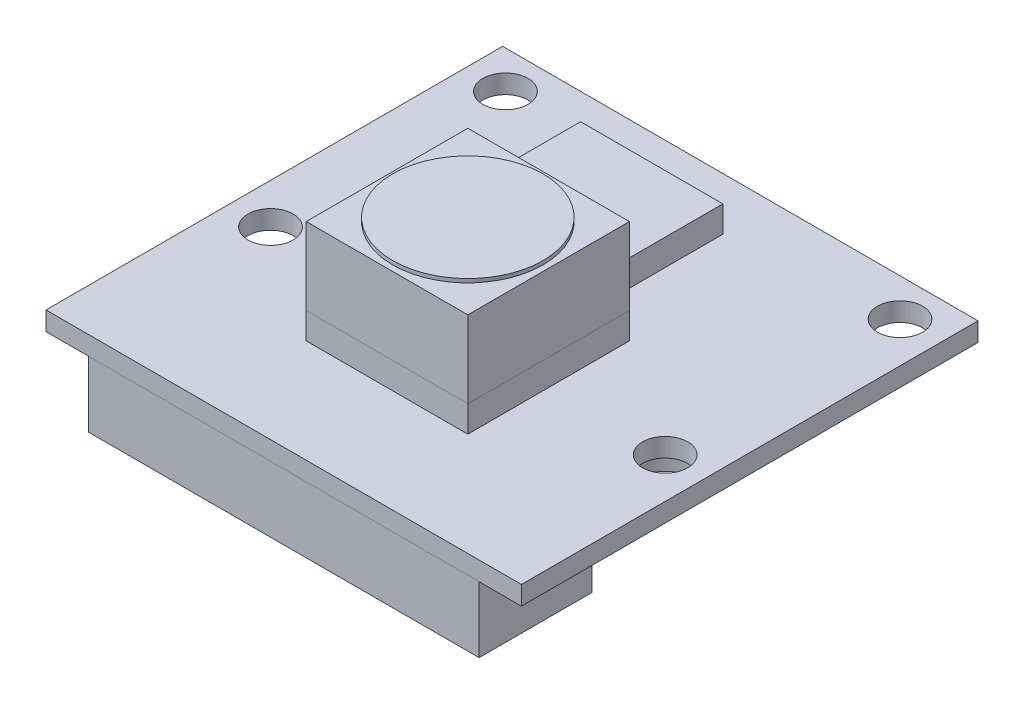
SolidWorks part; units mm, degrees
ref_plane "Plan de face" through (0, 0, 0) normal (0, 0, 1) x (1, 0, 0)
ref_plane "Plan de dessus" through (0, 0, 0) normal (0, 1, 0) x (1, 0, 0)
ref_plane "Plan de droite" through (0, 0, 0) normal (1, 0, 0) x (0, 0, -1)
sketch "Esquisse1" plane through (0, 0, 0) normal (0, 1, 0) x (1, 0, 0)
  line L0 (-12.65, -12.15) -> (12.65, 12.15) construction
  line L1 (-12.65, 12.15) -> (12.65, 12.15)
  line L2 (-12.65, 12.15) -> (-12.65, -12.15)
  line L3 (-12.65, -12.15) -> (12.65, -12.15)
  line L4 (12.65, 12.15) -> (12.65, -12.15)
  point P4 (0, 0)
  dimension "D1" = 25.3
  dimension "D2" = 24.3
extrude "Boss.-Extru.1" add sketch "Esquisse1" along normal blind 1
hole_wizard "Dégagement M21" positions "Esquisse2" profile "Esquisse3" hole size "M2" standard "Ansi Metric" end condition through all
sketch "Esquisse2" plane through (0, 1, 0) normal (0, 1, 0) x (1, 0, 0)
  line L0 (0, 0) -> (0, 3.03) construction
  line L1 (12.65, 12.15) -> (-12.65, 12.15) construction
  point P0 (-10.5, 10.15)
  point P8 (10.5, 10.15)
  point P9 (-10.5, -2.35)
  point P11 (10.5, -2.35)
  dimension "D1" = 21
  dimension "D2" = 12.5
  dimension "D3" = 2
sketch "Esquisse3" plane through (-10.5, 1, -10.15) normal (1, 0, 0) x (0, 0, 1)
  line L0 (0, 0) -> (0, 1)
  line L1 (0, 1) -> (1.2, 1)
  line L2 (1.2, 1) -> (1.2, 0)
  line L5 (1.2, 0) -> (0, 0)
  line L11 (0, -6.35) -> (0, 107.95) construction
  dimension "Diamètre du perçage jusqu'au prochain" = 2.4
  dimension "Profondeur du perçage jusqu'au prochain" = 1
sketch "Esquisse4" plane through (0, 1, 0) normal (0, 1, 0) x (1, 0, 0)
  line L0 (-5.7, 9.35) -> (-5.7, 5.8486)
  line L5 (-5.7, 5.8486) -> (-4.3, 5.8486)
  line L6 (-4.3, 5.8486) -> (-4.3, -6.65)
  line L7 (-4.3, -6.65) -> (4.3, -6.65)
  line L9 (1.8706, 9.35) -> (-5.7, 9.35)
  line L10 (1.8706, 9.35) -> (1.8706, 1.95)
  line L11 (1.8706, 1.95) -> (4.3, 1.95)
  line L12 (4.3, 1.95) -> (4.3, -6.65)
  line L14 (10.5, -2.35) -> (4.3, -2.35) construction
  point P2 (0, -6.65)
  dimension "D1" = 16
  dimension "D2" = 10
  dimension "D3" = 8.6
extrude "Boss.-Extru.2" add sketch "Esquisse4" along normal blind 1.4 separate body
sketch "Esquisse5" plane through (0, 2.4, 0) normal (0, 1, 0) x (1, 0, 0)
  line L0 (-4.3, -6.65) -> (4.3, -6.65) construction
  line L1 (4.3, 1.95) -> (-4.3, 1.95)
  line L2 (4.3, 1.95) -> (4.3, -6.65)
  line L3 (4.3, -6.65) -> (-4.3, -6.65)
  line L4 (-4.3, 1.95) -> (-4.3, -6.65)
  point P6 (-4.3, -6.65)
extrude "Boss.-Extru.3" add sketch "Esquisse5" along normal blind 4.1 separate body
sketch "Esquisse6" plane through (0, 6.5, 0) normal (0, 1, 0) x (1, 0, 0)
  line L0 (-4.3, -6.65) -> (4.3, 1.95) construction
  circle A0 centre (0, -2.35) radius 4
  point P6 (0, -2.25)
  point P7 (3.9141, 1.3268)
  point P8 (4.3, 1.95)
  point P10 (-4.3, -6.65)
  dimension "D1" = 8
extrude "Boss.-Extru.4" add sketch "Esquisse6" along normal blind 0.2 separate body
sketch "Esquisse8" plane through (0, 0, 0) normal (0, -1, 0) x (-1, 0, 0)
  line L0 (12.65, -12.15) -> (-12.65, -12.15) construction
  line L1 (-10.4, -6.15) -> (10.4, -6.15)
  line L2 (-10.4, -6.15) -> (-10.4, -12.15)
  line L3 (-10.4, -12.15) -> (10.4, -12.15)
  line L4 (10.4, -6.15) -> (10.4, -12.15)
  point P4 (0, -6.15)
  dimension "D1" = 20.8
  dimension "D2" = 6
extrude "Boss.-Extru.5" add sketch "Esquisse8" along normal blind 3.5 separate body
sketch "Esquisse9" plane through (0, 0, 0) normal (0, -1, 0) x (1, 0, 0)
  line L0 (-10.5, -0.1) -> (-10.5, -7.7)
  line L1 (-8.05, -10.15) -> (8.05, -10.15)
  line L2 (10.5, -7.7) -> (10.5, -0.1)
  line L3 (8.05, 2.35) -> (-8.05, 2.35)
  arc A0 (-10.5, -0.1) -> (-8.05, 2.35) centre (-10.5, 2.35) ccw
  arc A1 (8.05, 2.35) -> (10.5, -0.1) centre (10.5, 2.35) ccw
  arc A2 (10.5, -7.7) -> (8.05, -10.15) centre (10.5, -10.15) ccw
  arc A3 (-8.05, -10.15) -> (-10.5, -7.7) centre (-10.5, -10.15) ccw
  dimension "D1" = 4.9
extrude "Boss.-Extru.6" add sketch "Esquisse9" along normal blind 1.5 separate body
